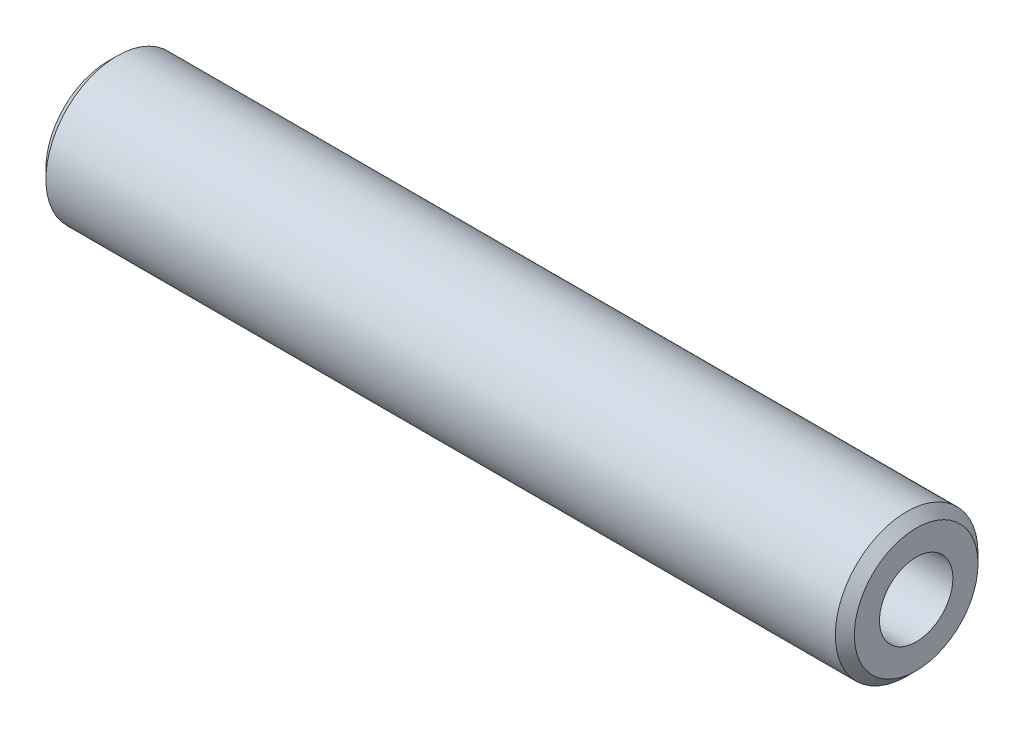
SolidWorks part; units mm, degrees
material "6061-T6 (SS)"
ref_plane "Front Plane" through (0, 0, 0) normal (0, 0, 1) x (1, 0, 0)
ref_plane "Top Plane" through (0, 0, 0) normal (0, 1, 0) x (1, 0, 0)
ref_plane "Right Plane" through (0, 0, 0) normal (1, 0, 0) x (0, 0, -1)
sketch "Sketch1" plane through (0, 0, 0) normal (1, 0, 0) x (0, 0, -1)
  circle A0 centre (0, 0) radius 9.525
  circle A1 centre (0, 0) radius 4.9022
  dimension "D1" = 9.8044
  dimension "D2" = 19.05
extrude "Boss-Extrude1" add sketch "Sketch1" along normal blind 107.95
chamfer "Chamfer1" distance 1.27 angle 45 2 edges at (107.95, 0, -9.525) (0, 0, -9.525)
